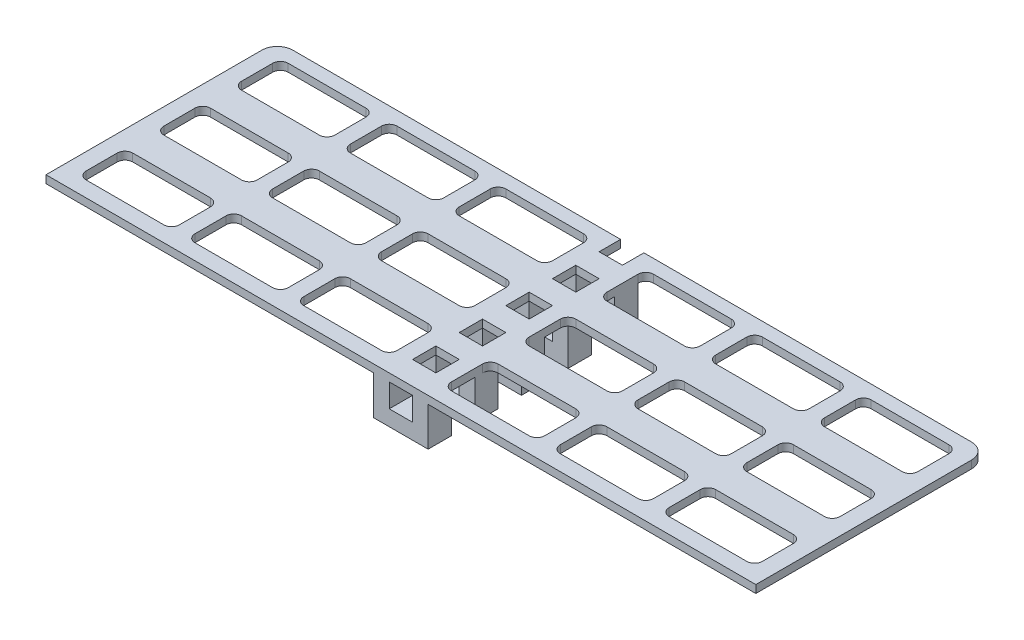
SolidWorks part; units mm, degrees
material "Balsa"
ref_plane "Front Plane" through (0, 0, 0) normal (0, 0, 1) x (1, 0, 0)
ref_plane "Top Plane" through (0, 0, 0) normal (0, 1, 0) x (1, 0, 0)
ref_plane "Right Plane" through (0, 0, 0) normal (1, 0, 0) x (0, 0, -1)
sketch "Sketch1" plane through (0, 0, 0) normal (0, 1, 0) x (1, 0, 0)
  line L0 (0, 0) -> (280.416, 0)
  line L1 (267.716, 188.976) -> (0, 188.976)
  line L2 (0, 188.976) -> (0, 0)
  line L3 (280.416, 0) -> (280.416, 176.276)
  arc A0 (267.716, 188.976) -> (280.416, 176.276) centre (267.716, 176.276) cw
  point P7 (280.416, 188.976)
  dimension "D4" = 12.7
  dimension "D1" = 188.976
  dimension "D2" = 280.416
  dimension "D3" = 188.976
extrude "Boss-Extrude1" add sketch "Sketch1" along normal blind 6.35
sketch "Sketch2" plane through (0, 6.35, 0) normal (0, 1, 0) x (1, 0, 0)
  line L0 (0, 188.976) -> (0, 0) construction
  line L9 (0, 0) -> (280.416, 0) construction
  line L76 (101.6, 19.05) -> (101.6, 44.45)
  line L91 (19.05, 12.7) -> (82.55, 12.7)
  line L92 (12.7, 19.05) -> (12.7, 44.45)
  line L93 (19.05, 50.8) -> (82.55, 50.8)
  line L94 (88.9, 19.05) -> (88.9, 44.45)
  line L95 (107.95, 12.7) -> (171.45, 12.7)
  line L96 (177.8, 19.05) -> (177.8, 44.45)
  line L97 (107.95, 50.8) -> (171.45, 50.8)
  line L98 (190.5, 19.05) -> (190.5, 44.45)
  line L99 (196.85, 12.7) -> (260.35, 12.7)
  line L100 (266.7, 19.05) -> (266.7, 44.45)
  line L101 (196.85, 50.8) -> (260.35, 50.8)
  line L102 (101.6, 82.55) -> (101.6, 107.95)
  line L103 (107.95, 76.2) -> (171.45, 76.2)
  line L104 (177.8, 82.55) -> (177.8, 107.95)
  line L105 (107.95, 114.3) -> (171.45, 114.3)
  line L106 (190.5, 82.55) -> (190.5, 107.95)
  line L107 (196.85, 76.2) -> (260.35, 76.2)
  line L108 (266.7, 82.55) -> (266.7, 107.95)
  line L109 (196.85, 114.3) -> (260.35, 114.3)
  line L110 (101.6, 146.05) -> (101.6, 171.45)
  line L111 (107.95, 139.7) -> (171.45, 139.7)
  line L112 (177.8, 146.05) -> (177.8, 171.45)
  line L113 (107.95, 177.8) -> (171.45, 177.8)
  line L114 (190.5, 146.05) -> (190.5, 171.45)
  line L115 (196.85, 139.7) -> (260.35, 139.7)
  line L116 (266.7, 146.05) -> (266.7, 171.45)
  line L117 (196.85, 177.8) -> (260.35, 177.8)
  line L118 (12.7, 82.55) -> (12.7, 107.95)
  line L119 (19.05, 76.2) -> (82.55, 76.2)
  line L120 (88.9, 82.55) -> (88.9, 107.95)
  line L121 (19.05, 114.3) -> (82.55, 114.3)
  line L122 (12.7, 146.05) -> (12.7, 171.45)
  line L123 (19.05, 139.7) -> (82.55, 139.7)
  line L124 (88.9, 146.05) -> (88.9, 171.45)
  line L125 (19.05, 177.8) -> (82.55, 177.8)
  line L126 (12.7, 19.05) -> (12.7, 82.55) construction
  arc A0 (82.55, 12.7) -> (88.9, 19.05) centre (82.55, 19.05) ccw
  arc A1 (19.05, 12.7) -> (12.7, 19.05) centre (19.05, 19.05) cw
  arc A2 (12.7, 44.45) -> (19.05, 50.8) centre (19.05, 44.45) cw
  arc A3 (82.55, 50.8) -> (88.9, 44.45) centre (82.55, 44.45) cw
  arc A4 (101.6, 44.45) -> (107.95, 50.8) centre (107.95, 44.45) cw
  arc A5 (107.95, 12.7) -> (101.6, 19.05) centre (107.95, 19.05) cw
  arc A6 (171.45, 12.7) -> (177.8, 19.05) centre (171.45, 19.05) ccw
  arc A7 (171.45, 50.8) -> (177.8, 44.45) centre (171.45, 44.45) cw
  arc A8 (190.5, 44.45) -> (196.85, 50.8) centre (196.85, 44.45) cw
  arc A9 (196.85, 12.7) -> (190.5, 19.05) centre (196.85, 19.05) cw
  arc A10 (260.35, 12.7) -> (266.7, 19.05) centre (260.35, 19.05) ccw
  arc A11 (260.35, 50.8) -> (266.7, 44.45) centre (260.35, 44.45) cw
  arc A12 (101.6, 107.95) -> (107.95, 114.3) centre (107.95, 107.95) cw
  arc A13 (107.95, 76.2) -> (101.6, 82.55) centre (107.95, 82.55) cw
  arc A14 (171.45, 76.2) -> (177.8, 82.55) centre (171.45, 82.55) ccw
  arc A15 (171.45, 114.3) -> (177.8, 107.95) centre (171.45, 107.95) cw
  arc A16 (190.5, 107.95) -> (196.85, 114.3) centre (196.85, 107.95) cw
  arc A17 (196.85, 76.2) -> (190.5, 82.55) centre (196.85, 82.55) cw
  arc A18 (260.35, 76.2) -> (266.7, 82.55) centre (260.35, 82.55) ccw
  arc A19 (260.35, 114.3) -> (266.7, 107.95) centre (260.35, 107.95) cw
  arc A20 (101.6, 171.45) -> (107.95, 177.8) centre (107.95, 171.45) cw
  arc A21 (107.95, 139.7) -> (101.6, 146.05) centre (107.95, 146.05) cw
  arc A22 (171.45, 139.7) -> (177.8, 146.05) centre (171.45, 146.05) ccw
  arc A23 (171.45, 177.8) -> (177.8, 171.45) centre (171.45, 171.45) cw
  arc A24 (190.5, 171.45) -> (196.85, 177.8) centre (196.85, 171.45) cw
  arc A25 (196.85, 139.7) -> (190.5, 146.05) centre (196.85, 146.05) cw
  arc A26 (260.35, 139.7) -> (266.7, 146.05) centre (260.35, 146.05) ccw
  arc A27 (260.35, 177.8) -> (266.7, 171.45) centre (260.35, 171.45) cw
  arc A28 (12.7, 107.95) -> (19.05, 114.3) centre (19.05, 107.95) cw
  arc A29 (19.05, 76.2) -> (12.7, 82.55) centre (19.05, 82.55) cw
  arc A30 (82.55, 76.2) -> (88.9, 82.55) centre (82.55, 82.55) ccw
  arc A31 (82.55, 114.3) -> (88.9, 107.95) centre (82.55, 107.95) cw
  arc A32 (12.7, 171.45) -> (19.05, 177.8) centre (19.05, 171.45) cw
  arc A33 (19.05, 139.7) -> (12.7, 146.05) centre (19.05, 146.05) cw
  arc A34 (82.55, 139.7) -> (88.9, 146.05) centre (82.55, 146.05) ccw
  arc A35 (82.55, 177.8) -> (88.9, 171.45) centre (82.55, 171.45) cw
  point P10 (88.9, 12.7)
  point P13 (12.7, 12.7)
  point P16 (12.7, 50.8)
  point P19 (101.6, 31.75)
  dimension "D7" = 3
  dimension "D5" = 6.35
  dimension "D1" = 12.7
  dimension "D2" = 76.2
  dimension "D3" = 12.7
  dimension "D4" = 38.1
  dimension "D8" = 63.5
  dimension "D9" = 25.4
  dimension "D10" = 12.7
  dimension "D6" = 3
extrude "Cut-Extrude1" cut sketch "Sketch2" against normal up to surface (6.35 mm away) up to face at (166.2357, 0, -111.3717)
sketch "Sketch3" plane through (0, 6.35, 0) normal (0, 1, 0) x (1, 0, 0)
  line L2 (0, 19.05) -> (0, 38.1)
  line L3 (0, 0) -> (-19.05, 0)
  line L4 (0, 0) -> (0, 19.05)
  line L5 (0, 19.05) -> (-19.05, 19.05)
  line L6 (-19.05, 0) -> (-19.05, 19.05)
  line L7 (0, 19.05) -> (-19.05, 19.05)
  line L8 (-19.05, 19.05) -> (-19.05, 38.1)
  line L9 (0, 38.1) -> (-19.05, 38.1)
  line L10 (0, 38.1) -> (0, 57.15)
  line L11 (0, 38.1) -> (-19.05, 38.1)
  line L12 (-19.05, 38.1) -> (-19.05, 57.15)
  line L13 (0, 57.15) -> (-19.05, 57.15)
  line L14 (0, 57.15) -> (0, 76.2)
  line L15 (0, 57.15) -> (-19.05, 57.15)
  line L16 (-19.05, 57.15) -> (-19.05, 76.2)
  line L17 (0, 76.2) -> (-19.05, 76.2)
  line L18 (0, 76.2) -> (0, 95.25)
  line L19 (0, 76.2) -> (-19.05, 76.2)
  line L20 (-19.05, 76.2) -> (-19.05, 95.25)
  line L21 (0, 95.25) -> (-19.05, 95.25)
  line L22 (0, 95.25) -> (0, 114.3)
  line L23 (0, 95.25) -> (-19.05, 95.25)
  line L24 (-19.05, 95.25) -> (-19.05, 114.3)
  line L25 (0, 114.3) -> (-19.05, 114.3)
  line L26 (0, 114.3) -> (0, 133.35)
  line L27 (0, 114.3) -> (-19.05, 114.3)
  line L28 (-19.05, 114.3) -> (-19.05, 133.35)
  line L29 (0, 133.35) -> (-19.05, 133.35)
  line L30 (0, 133.35) -> (0, 152.4)
  line L31 (0, 133.35) -> (-19.05, 133.35)
  line L32 (-19.05, 133.35) -> (-19.05, 152.4)
  line L33 (0, 152.4) -> (-19.05, 152.4)
  line L34 (0, 152.4) -> (0, 171.45)
  line L35 (0, 152.4) -> (-19.05, 152.4)
  line L36 (-19.05, 152.4) -> (-19.05, 171.45)
  line L37 (0, 171.45) -> (-19.05, 171.45)
  line L38 (0, 171.45) -> (0, 190.5)
  line L39 (0, 171.45) -> (-19.05, 171.45)
  line L40 (-19.05, 171.45) -> (-19.05, 190.5)
  line L41 (0, 190.5) -> (-19.05, 190.5)
  line L43 (0, 190.5) -> (-19.05, 190.5)
  line L74 (0, 190.5) -> (0, 209.55) [skipped]
  line L75 (-19.05, 190.5) -> (-19.05, 209.55) [skipped]
  line L76 (0, 209.55) -> (-19.05, 209.55) [skipped]
  line L77 (0, 209.55) -> (0, 228.6) [skipped]
  line L78 (0, 209.55) -> (-19.05, 209.55) [skipped]
  line L79 (-19.05, 209.55) -> (-19.05, 228.6) [skipped]
  line L80 (0, 228.6) -> (-19.05, 228.6) [skipped]
  line L81 (0, 228.6) -> (0, 247.65) [skipped]
  line L82 (0, 228.6) -> (-19.05, 228.6) [skipped]
  line L83 (-19.05, 228.6) -> (-19.05, 247.65) [skipped]
  line L84 (0, 247.65) -> (0, 266.7) [skipped]
  line L85 (0, 247.65) -> (-19.05, 247.65) [skipped]
  line L86 (-19.05, 247.65) -> (-19.05, 266.7) [skipped]
  line L87 (0, 266.7) -> (-19.05, 266.7) [skipped]
  line L88 (0, 266.7) -> (0, 285.75) [skipped]
  line L89 (0, 266.7) -> (-19.05, 266.7) [skipped]
  line L90 (-19.05, 266.7) -> (-19.05, 285.75) [skipped]
  line L91 (0, 285.75) -> (-19.05, 285.75) [skipped]
  line L92 (0, 285.75) -> (0, 304.8) [skipped]
  line L93 (0, 285.75) -> (-19.05, 285.75) [skipped]
  line L94 (-19.05, 285.75) -> (-19.05, 304.8) [skipped]
  line L95 (0, 304.8) -> (-19.05, 304.8) [skipped]
  line L96 (0, 304.8) -> (0, 323.85) [skipped]
  line L97 (0, 304.8) -> (-19.05, 304.8) [skipped]
  line L98 (-19.05, 304.8) -> (-19.05, 323.85) [skipped]
  line L99 (0, 323.85) -> (-19.05, 323.85) [skipped]
  line L100 (0, 323.85) -> (0, 342.9) [skipped]
  line L101 (0, 323.85) -> (-19.05, 323.85) [skipped]
  line L102 (-19.05, 323.85) -> (-19.05, 342.9) [skipped]
  line L103 (0, 342.9) -> (-19.05, 342.9) [skipped]
  line L104 (0, 247.65) -> (-19.05, 247.65) [skipped]
  dimension "D2" = 19.05
  dimension "D3" = 19.05
  dimension "D4" = 18
extrude "Boss-Extrude2" add sketch "Sketch3" against normal up to surface (6.35 mm away) up to face at (139.7, 0, -31.75)
ref_plane "Plane1" through (-9.525, 0, 0) normal (-1, 0, 0) x (0, 0, 1)
mirror "Mirror3" about plane through (-9.525, 0, 0) normal (-1, 0, 0) of "Boss-Extrude1"
mirror "Mirror2" about plane through (-9.525, 0, 0) normal (-1, 0, 0) of "Cut-Extrude1"
sketch "Sketch5" plane through (0, 0, 0) normal (0, 0, 1) x (1, 0, 0)
  line L0 (-299.466, 0) -> (280.416, 0) construction
  line L1 (0, 0) -> (-19.05, 0)
  line L2 (0, 0) -> (0, -19.05)
  line L3 (0, -19.05) -> (-19.05, -19.05)
  line L4 (-19.05, 0) -> (-19.05, -19.05)
  line L6 (-31.75, 0) -> (12.7, 0)
  line L7 (-31.75, 0) -> (-31.75, -31.75)
  line L8 (-31.75, -31.75) -> (12.7, -31.75)
  line L9 (-19.05, 0) -> (0, 0)
  line L10 (0, 0) -> (0, 6.35)
  line L11 (0, 6.35) -> (-19.05, 6.35)
  line L12 (-19.05, 6.35) -> (-19.05, 0)
  line L13 (-19.05, 0) -> (0, 0)
  line L14 (0, 0) -> (0, 6.35)
  line L15 (0, 6.35) -> (-19.05, 6.35)
  line L17 (12.7, 0) -> (12.7, -31.75)
  line L22 (-19.05, 6.35) -> (-19.05, 0)
  line M5 (-299.466, 0) -> (280.416, 0)
  dimension "D1" = 19.05
  dimension "D2" = 19.05
  dimension "D3" = 0
  dimension "D4" = 0
  dimension "D5" = 12.7
  dimension "D6" = 31.75
  dimension "D7" = 12.7
extrude "Boss-Extrude3" add sketch "Sketch5" against normal blind 19.05 contours L17 L2 L3 L4 L7 L8 M5
pattern_linear "LPattern1" count 9 spacing 38.1 along (0, 0, -1) of "Boss-Extrude3"
equation "\"D3@Sketch1\"=\"D1@Sketch1\""
